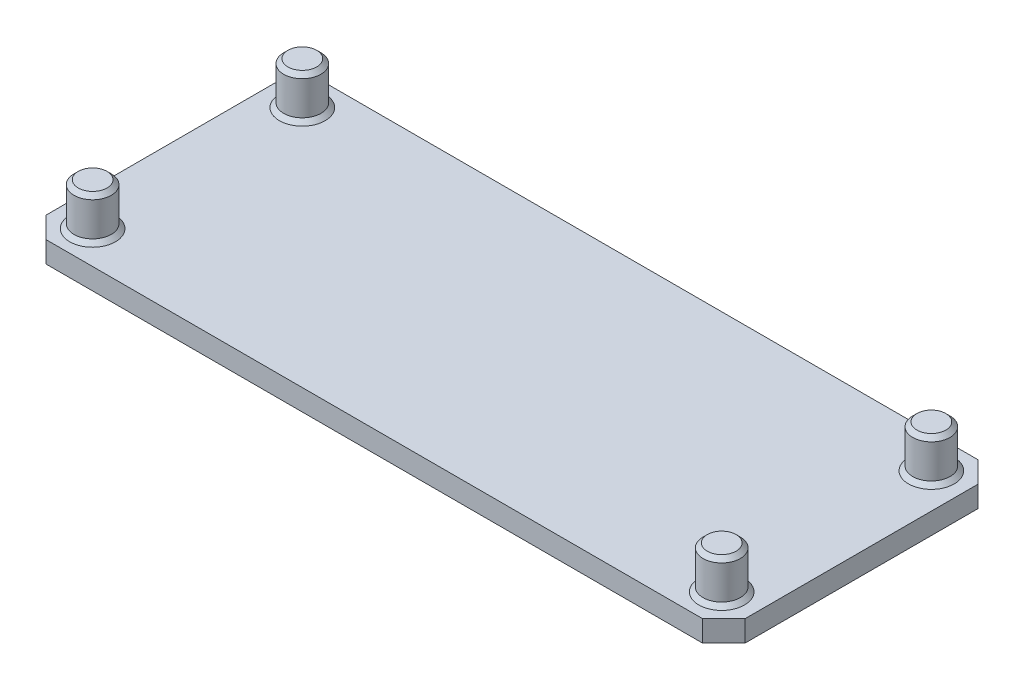
SolidWorks part; units mm, degrees
ref_plane "Front Plane" through (0, 0, 0) normal (0, 0, 1) x (1, 0, 0)
ref_plane "Top Plane" through (0, 0, 0) normal (0, 1, 0) x (1, 0, 0)
ref_plane "Right Plane" through (0, 0, 0) normal (1, 0, 0) x (0, 0, -1)
sketch "Sketch2" plane through (0, 0, 0) normal (0, 1, 0) x (1, 0, 0)
  line L1 (-82.5, -32.5) -> (82.5, -32.5)
  line L2 (-82.5, -32.5) -> (-82.5, 32.5)
  line L3 (-82.5, 32.5) -> (82.5, 32.5)
  line L4 (82.5, -32.5) -> (82.5, 32.5)
  line L5 (-82.5, -32.5) -> (82.5, 32.5) construction
  line L6 (-82.5, 32.5) -> (82.5, -32.5) construction
  point P0 (0, 0)
  dimension "D1" = 165
  dimension "D2" = 65
extrude "Boss-Extrude1" add sketch "Sketch2" along normal blind 5
sketch "Sketch3" plane through (0, 5, 0) normal (0, 1, 0) x (1, 0, 0)
  line L1 (-74.245, -24.75) -> (74.245, -24.75) construction
  line L2 (-74.245, -24.75) -> (-74.245, 24.75) construction
  line L3 (-74.245, 24.75) -> (74.245, 24.75) construction
  line L4 (74.245, -24.75) -> (74.245, 24.75) construction
  line L5 (-74.245, -24.75) -> (74.245, 24.75) construction
  line L6 (-74.245, 24.75) -> (74.245, -24.75) construction
  circle A0 centre (-74.245, 24.75) radius 4.4
  circle A1 centre (-74.245, -24.75) radius 4.4
  circle A2 centre (74.245, -24.75) radius 4.4
  circle A4 centre (74.245, 24.75) radius 4.4
  point P0 (0, 0)
  dimension "D3" = 8.8
  dimension "D1" = 49.5
  dimension "D2" = 148.49
extrude "Boss-Extrude2" add sketch "Sketch3" along normal blind 10
chamfer "Chamfer1" distance 1 angle 45 8 edges at (74.245, 5, 20.35) (74.245, 15, 29.15) (74.245, 5, -29.15) (74.245, 15, -20.35) (-74.245, 5, 20.35) (-74.245, 15, 29.15) (-74.245, 5, -29.15) (-74.245, 15, -20.35)
chamfer "Chamfer2" distance 5 angle 45 4 edges at (-82.5, 2.5, 32.5) (-82.5, 2.5, -32.5) (82.5, 2.5, 32.5) (82.5, 2.5, -32.5)
sketch "Sketch4" plane through (0, 0, 0) normal (0, -1, 0) x (1, 0, 0)
  line L0 (-82.5, 27.5) -> (-77.5, 27.5) construction
  line L1 (-77.5, 27.5) -> (-77.5, 32.5) construction
  line L3 (77.5, -27.5) -> (-77.5, -27.5) construction
  line L4 (77.5, -27.5) -> (77.5, 27.5) construction
  line L5 (77.5, 27.5) -> (-77.5, 27.5) construction
  line L6 (-77.5, -27.5) -> (-77.5, 27.5) construction
  line L7 (77.5, -27.5) -> (-77.5, 27.5) construction
  line L8 (77.5, 27.5) -> (-77.5, -27.5) construction
  circle A0 centre (-77.5, 27.5) radius 1
  circle A1 centre (-77.5, -27.5) radius 1
  circle A2 centre (77.5, -27.5) radius 1
  point P2 (0, 0)
  dimension "D1" = 2
extrude "Cut-Extrude1" cut sketch "Sketch4" against normal blind 2
sketch "Sketch5" plane through (0, 0, 0) normal (0, -1, 0) x (1, 0, 0)
  line L0 (-82.5, 0) -> (82.5, 0) construction
  line L1 (-82.5, -27.5) -> (-82.5, 27.5) construction
  line L2 (82.5, 27.5) -> (82.5, -27.5) construction
  line L4 (-59.25, 17.6092) -> (-74.5, 8.8046)
  line L5 (-74.5, 8.8046) -> (-74.5, -8.8046)
  line L6 (-74.5, -8.8046) -> (-59.25, -17.6092)
  line L7 (-59.25, -17.6092) -> (-44, -8.8046)
  line L8 (-44, -8.8046) -> (-44, 8.8046)
  line L9 (-44, 8.8046) -> (-59.25, 17.6092)
  line L10 (15, -6.4952) -> (15, 6.4952)
  line L11 (15, 6.4952) -> (3.75, 12.9904)
  line L12 (3.75, 12.9904) -> (-7.5, 6.4952)
  line L13 (-7.5, 6.4952) -> (-7.5, -6.4952)
  line L14 (-7.5, -6.4952) -> (3.75, -12.9904)
  line L15 (3.75, -12.9904) -> (15, -6.4952)
  circle A0 centre (-59.25, 0) radius 15.25 construction
  circle A1 centre (-25.75, 0) radius 10.25
  circle A2 centre (3.75, 0) radius 11.25 construction
  circle A3 centre (34.25, 0) radius 11.25
  circle A4 centre (59.25, 0) radius 5.75
  dimension "D3" = 20.5
  dimension "D7" = 22.5
  dimension "D9" = 11.5
  dimension "D1" = 30.5
  dimension "D2" = 8
  dimension "D4" = 18.25
  dimension "D5" = 22.5
  dimension "D6" = 18.25
  dimension "D8" = 19.25
  dimension "D10" = 25
extrude "Cut-Extrude2" cut sketch "Sketch5" against normal blind 2
